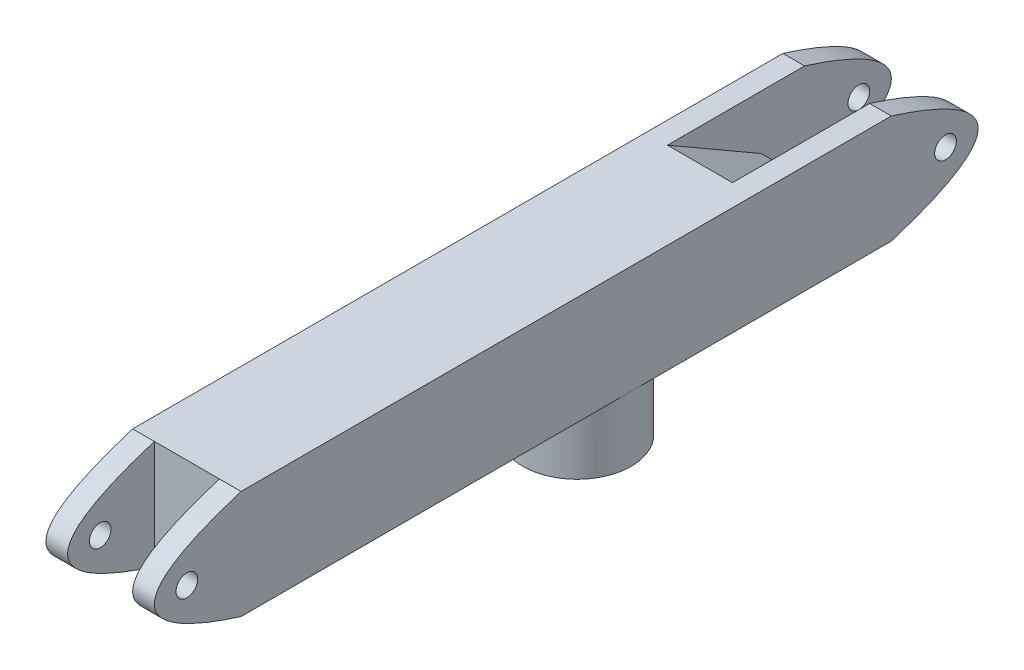
SolidWorks part; units mm, degrees
ref_plane "Front Plane" through (0, 0, 0) normal (0, 0, 1) x (1, 0, 0)
ref_plane "Top Plane" through (0, 0, 0) normal (0, 1, 0) x (1, 0, 0)
ref_plane "Right Plane" through (0, 0, 0) normal (1, 0, 0) x (0, 0, -1)
sketch "Sketch1" plane through (0, 0, 0) normal (1, 0, 0) x (0, 0, -1)
  line L0 (-255.8715, 42.046) -> (44.1285, 42.046)
  line L3 (-255.8715, -7.954) -> (44.1285, -7.954)
  circle A0 centre (-280.8715, 17.046) radius 5
  circle A1 centre (69.1285, 17.046) radius 5
  spline S0 degree 2 poles (44.1285, 42.046) (124.1285, 17.046) (44.1285, -7.954) knots 0 0 0 1 1 1
  spline S1 degree 2 poles (-255.8715, 42.046) (-335.8715, 17.046) (-255.8715, -7.954) knots 0 0 0 1 1 1
  dimension "D6" = 40
  dimension "D8" = 10
  dimension "D9" = 15
  dimension "D1" = 300
  dimension "D2" = 50
  dimension "D3" = 25
  dimension "D4" = 40
  dimension "D5" = 15
  dimension "D7" = 0
extrude "Boss-Extrude1" add sketch "Sketch1" along normal blind 50
sketch "Sketch2" plane through (0, 0, 0) normal (0, 1, 0) x (1, 0, 0)
  line L0 (50, 84.1285) -> (0, 84.1285) construction
  line L1 (10, 84.1285) -> (40, 84.1285)
  line L2 (10, 84.1285) -> (10, 24.1285)
  line L3 (10, 24.1285) -> (40, 24.1285)
  line L4 (40, 84.1285) -> (40, 24.1285)
  line L6 (0, 84.1285) -> (0, 44.1285) construction
  point P11 (-68.6945, 37.4654)
  dimension "D1" = 10
  dimension "D2" = 10
  dimension "D3" = 60
extrude "Cut-Extrude1" cut sketch "Sketch2" along normal blind 52 and the other way blind 35
sketch "Sketch3" plane through (0, -7.954, 0) normal (0, -1, 0) x (1, 0, 0)
  line L0 (50, 295.8715) -> (0, 295.8715) construction
  line L1 (10, 295.8715) -> (40, 295.8715)
  line L2 (10, 295.8715) -> (10, 255.8715)
  line L3 (10, 255.8715) -> (40, 255.8715)
  line L4 (40, 295.8715) -> (40, 255.8715)
  line L5 (50, 255.8715) -> (0, 255.8715) construction
  dimension "D1" = 10
  dimension "D2" = 10
extrude "Cut-Extrude2" cut sketch "Sketch3" against normal blind 52
sketch "Sketch4" plane through (0, 0, 0) normal (-1, 0, 0) x (0, 0, 1)
  line L1 (-44.1285, 42.046) -> (255.8715, 42.046) construction
  line L5 (-24.1285, 17.046) -> (-24.1285, 42.046)
  line L6 (-24.1285, 42.046) -> (19.1728, 42.046)
  line L7 (-24.1285, 17.046) -> (19.1728, 42.046)
  line L8 (-24.1285, -7.954) -> (-24.1285, 42.046) construction
  dimension "D1" = 25
  dimension "D2" = 60
  dimension "D3" = 0
extrude "Cut-Extrude3" cut sketch "Sketch4" against normal blind 30 from offset 10 offset against normal yes
sketch "Sketch5" plane through (0, 0, 0) normal (-1, 0, 0) x (0, 0, 1)
  line L0 (-24.1285, -7.954) -> (-24.1285, 17.046)
  line L1 (-24.1285, 17.046) -> (19.1728, -7.954)
  line L2 (255.8715, -7.954) -> (-44.1285, -7.954) construction
  line L3 (19.1728, -7.954) -> (-24.1285, -7.954)
  line L5 (-24.1285, -7.954) -> (-24.1285, 17.046) construction
  dimension "D1" = 25
  dimension "D2" = 60
  dimension "D3" = 0
extrude "Cut-Extrude4" cut sketch "Sketch5" against normal blind 30 from offset 10 offset against normal yes
sketch "Sketch6" plane through (0, -7.954, 0) normal (0, -1, 0) x (1, 0, 0)
  line L0 (0, 255.8715) -> (0, -44.1285) construction
  line L1 (0, -84.1285) -> (10, -84.1285) construction
  circle A0 centre (25, 75.8715) radius 25
  dimension "D1" = 50
  dimension "D2" = 25
  dimension "D3" = 160
extrude "Boss-Extrude2" add sketch "Sketch6" along normal blind 30
